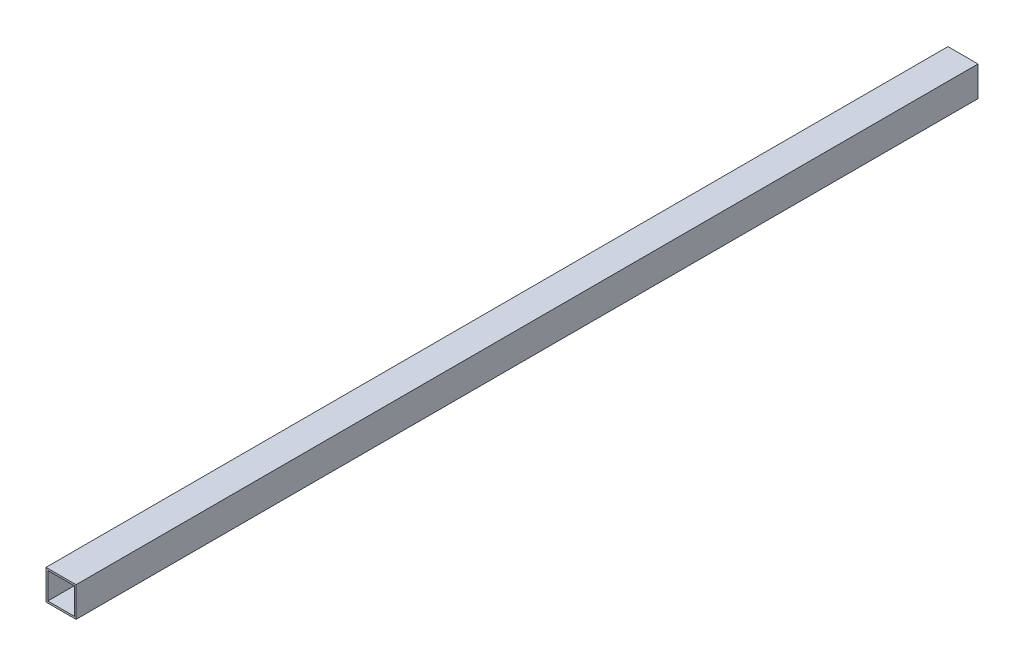
SolidWorks part; units mm, degrees
material "1.5714 (16NiCr4)"
ref_plane "Alzado" through (0, 0, 0) normal (0, 0, 1) x (1, 0, 0)
ref_plane "Planta" through (0, 0, 0) normal (0, 1, 0) x (1, 0, 0)
ref_plane "Vista lateral" through (0, 0, 0) normal (1, 0, 0) x (0, 0, -1)
sketch "Croquis1" plane through (0, 0, 0) normal (0, 0, 1) x (1, 0, 0)
  line L0 (-22, -22) -> (-22, 22)
  line L1 (-25, -25) -> (25, -25)
  line L2 (-25, -25) -> (-25, 25)
  line L3 (-25, 25) -> (25, 25)
  line L4 (25, -25) -> (25, 25)
  line L5 (-25, -25) -> (25, 25) construction
  line L6 (-25, 25) -> (25, -25) construction
  line L7 (-22, 22) -> (22, 22)
  line L8 (22, -22) -> (22, 22)
  line L9 (-22, -22) -> (22, -22)
  point P0 (0, 0)
  dimension "D1" = 50
  dimension "D2" = 50
  dimension "D3" = 3
extrude "Saliente-Extruir1" add sketch "Croquis1" along normal mid plane 1500
